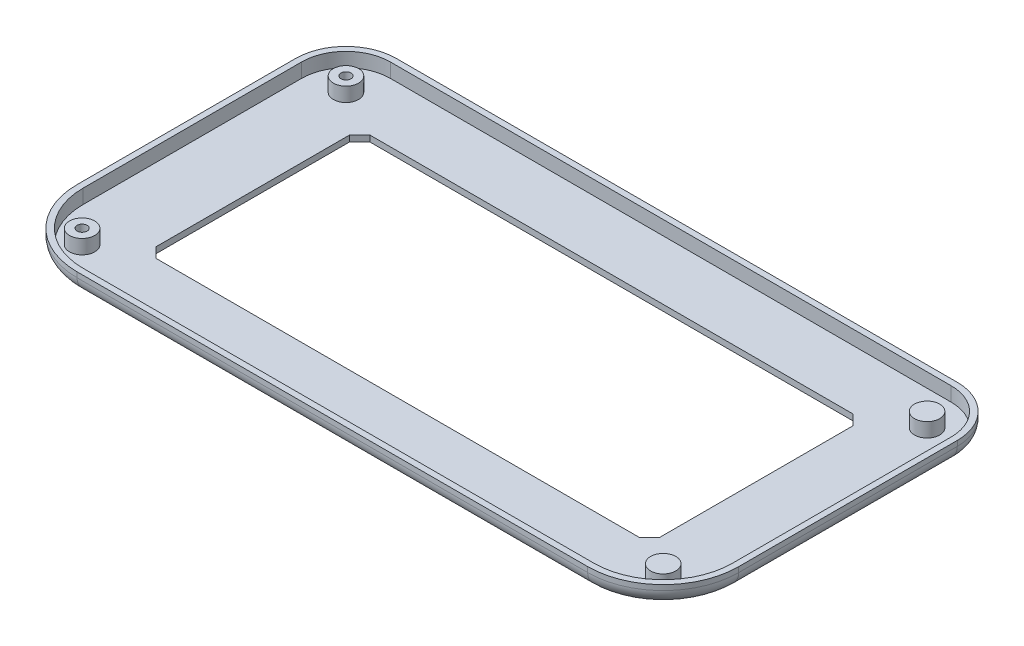
SolidWorks part; units mm, degrees
ref_plane "Plano frontal" through (0, 0, 0) normal (0, 0, 1) x (1, 0, 0)
ref_plane "Plano superior" through (0, 0, 0) normal (0, 1, 0) x (1, 0, 0)
ref_plane "Plano direito" through (0, 0, 0) normal (1, 0, 0) x (0, 0, -1)
sketch "Esboço1" plane through (0, 0, 0) normal (0, 1, 0) x (1, 0, 0)
  line L1 (-65.7, -34.2) -> (65.7, -34.2)
  line L2 (-65.7, -34.2) -> (-65.7, 34.2)
  line L3 (-65.7, 34.2) -> (65.7, 34.2)
  line L4 (65.7, -34.2) -> (65.7, 34.2)
  line L5 (-65.7, -34.2) -> (65.7, 34.2) construction
  line L6 (-65.7, 34.2) -> (65.7, -34.2) construction
  point P0 (0, 0)
  dimension "D1" = 131.4
  dimension "D2" = 68.4
extrude "Base" add sketch "Esboço1" along normal blind 1.2
fillet "Filete1" radius 15 1 edges at (65.7, 0.6, 34.2)
fillet "Filete2" radius 15 1 edges at (-65.7, 0.6, 34.2)
fillet "Filete3" radius 10 1 edges at (65.7, 0.6, -34.2)
fillet "Filete4" radius 10 1 edges at (-65.7, 0.6, -34.2)
sketch "Esboço5" plane through (0, 1.2, 0) normal (0, 1, 0) x (1, 0, 0)
  line L0 (55.7, 33) -> (-55.7, 33)
  line L1 (-64.5, 24.2) -> (-64.5, -19.2)
  line L2 (-50.7, -33) -> (50.7, -33)
  line L3 (64.5, -19.2) -> (64.5, 24.2)
  line L4 (55.7, 34.2) -> (-55.7, 34.2)
  line L5 (-65.7, 24.2) -> (-65.7, -19.2)
  line L6 (-50.7, -34.2) -> (50.7, -34.2)
  line L7 (65.7, -19.2) -> (65.7, 24.2)
  line L8 (55.7, 34.2) -> (-55.7, 34.2)
  line L9 (-65.7, 24.2) -> (-65.7, -19.2)
  line L10 (-50.7, -34.2) -> (50.7, -34.2)
  line L11 (65.7, -19.2) -> (65.7, 24.2)
  arc A0 (-55.7, 33) -> (-64.5, 24.2) centre (-55.7, 24.2) ccw
  arc A1 (-64.5, -19.2) -> (-50.7, -33) centre (-50.7, -19.2) ccw
  arc A2 (50.7, -33) -> (64.5, -19.2) centre (50.7, -19.2) ccw
  arc A3 (64.5, 24.2) -> (55.7, 33) centre (55.7, 24.2) ccw
  arc A4 (-55.7, 34.2) -> (-65.7, 24.2) centre (-55.7, 24.2) ccw
  arc A5 (-65.7, -19.2) -> (-50.7, -34.2) centre (-50.7, -19.2) ccw
  arc A6 (50.7, -34.2) -> (65.7, -19.2) centre (50.7, -19.2) ccw
  arc A7 (65.7, 24.2) -> (55.7, 34.2) centre (55.7, 24.2) ccw
  arc A8 (-55.7, 34.2) -> (-65.7, 24.2) centre (-55.7, 24.2) ccw
  arc A9 (-65.7, -19.2) -> (-50.7, -34.2) centre (-50.7, -19.2) ccw
  arc A10 (50.7, -34.2) -> (65.7, -19.2) centre (50.7, -19.2) ccw
  arc A11 (65.7, 24.2) -> (55.7, 34.2) centre (55.7, 24.2) ccw
  dimension "D1" = 0
extrude "Paredes" add sketch "Esboço5" along normal blind 10
fillet "Filete da base" radius 3 8 edges at (65.7, 0, -2.5) (61.3066, 0, 29.8066) (0, 0, 34.2) (-61.3066, 0, 29.8066) (0, 0, -34.2) (62.7711, 0, -31.2711) (-65.7, 0, -2.5) (-62.7711, 0, -31.2711)
sketch "Esboço6" plane through (0, 1.2, 0) normal (0, 1, 0) x (1, 0, 0)
  line L0 (65.7, -19.2) -> (65.7, 24.2) construction
  line L1 (-57.7, -26.2) -> (57.7, -26.2)
  line L2 (-57.7, -26.2) -> (-57.7, 26.2)
  line L3 (-57.7, 26.2) -> (57.7, 26.2)
  line L4 (57.7, -26.2) -> (57.7, 26.2)
  line L5 (-57.7, -26.2) -> (57.7, 26.2) construction
  line L6 (-57.7, 26.2) -> (57.7, -26.2) construction
  line L7 (55.7, 34.2) -> (-55.7, 34.2) construction
  circle A0 centre (-57.7, 26.2) radius 2.5
  circle A1 centre (-57.7, -26.2) radius 2.5
  circle A2 centre (57.7, 26.2) radius 2.5
  circle A3 centre (57.7, -26.2) radius 2.5
  point P0 (0, 0)
  arc M6 (-64.5, -19.2) -> (-50.7, -33) centre (-50.7, -19.2) ccw
  arc M8 (50.7, -33) -> (64.5, -19.2) centre (50.7, -19.2) ccw
  dimension "D1" = 5
  dimension "D2" = 8
  dimension "D3" = 8
extrude "Suporte dos parafusos" add sketch "Esboço6" along normal blind 10 contours L3 A0 L2 | L2 A0 L3 | L4 A2 L3 | L3 A2 L4 | A3 L4 L1 M8 | L4 A3 L1 | L2 A1 L1 M6 | L1 A1 L2
sketch "Esboço7" plane through (0, 11.2, 0) normal (0, 1, 0) x (1, 0, 0)
  circle A0 centre (-57.7, 26.2) radius 1
  circle A1 centre (-57.7, -26.2) radius 1
  circle A2 centre (57.7, -26.2) radius 1
  circle A3 centre (57.7, 26.2) radius 1
  dimension "D1" = 2
extrude "Furo para os parafusos" cut sketch "Esboço7" against normal blind 6
sketch "Esboço8" plane through (0, 1.2, 0) normal (0, 1, 0) x (1, 0, 0)
  line L1 (-50, -21.2247) -> (50, -21.2247)
  line L2 (-50, -21.2247) -> (-50, 21.2247)
  line L3 (-50, 21.2247) -> (50, 21.2247)
  line L4 (50, -21.2247) -> (50, 21.2247)
  line L5 (-50, -21.2247) -> (50, 21.2247) construction
  line L6 (-50, 21.2247) -> (50, -21.2247) construction
  point P0 (0, 0)
  point P6 (0, 21.2247)
  point P11 (0, -21.2247)
  dimension "D1" = 100
extrude "Corte-extrusão1" cut sketch "Esboço8" against normal blind 10
sketch "Esboço9" plane through (0, 0, 34.2) normal (0, 0, 1) x (1, 0, 0)
  line L0 (-50.7, 11.2) -> (50.7, 11.2) construction
  line L1 (-67.4971, 18.3734) -> (67.4971, 18.3734)
  line L2 (-67.4971, 18.3734) -> (-67.4971, 4.0266)
  line L3 (-67.4971, 4.0266) -> (67.4971, 4.0266)
  line L4 (67.4971, 18.3734) -> (67.4971, 4.0266)
  line L5 (-67.4971, 18.3734) -> (67.4971, 4.0266) construction
  line L6 (-67.4971, 4.0266) -> (67.4971, 18.3734) construction
  point P0 (0, 11.2)
extrude "Corte-extrusão2" cut sketch "Esboço9" against normal through all
sketch "Esboço10" plane through (0, 4.0266, 0) normal (0, 1, 0) x (1, 0, 0)
  circle A0 centre (-57.7, 26.2) radius 1
  circle A1 centre (-57.7, -26.2) radius 1
  dimension "D1" = 2
  dimension "D2" = 2
chamfer "Chanfro8" distance 2 angle 45 1 edges at (-50, 0.6, -21.2247)
chamfer "Chanfro9" distance 2 angle 45 1 edges at (50, 0.6, -21.2247)
chamfer "Chanfro10" distance 2 angle 45 1 edges at (50, 0.6, 21.2247)
chamfer "Chanfro11" distance 2 angle 45 1 edges at (-50, 0.6, 21.2247)
extrude "Corte-extrusão4" cut sketch "Esboço10" against normal blind 2
